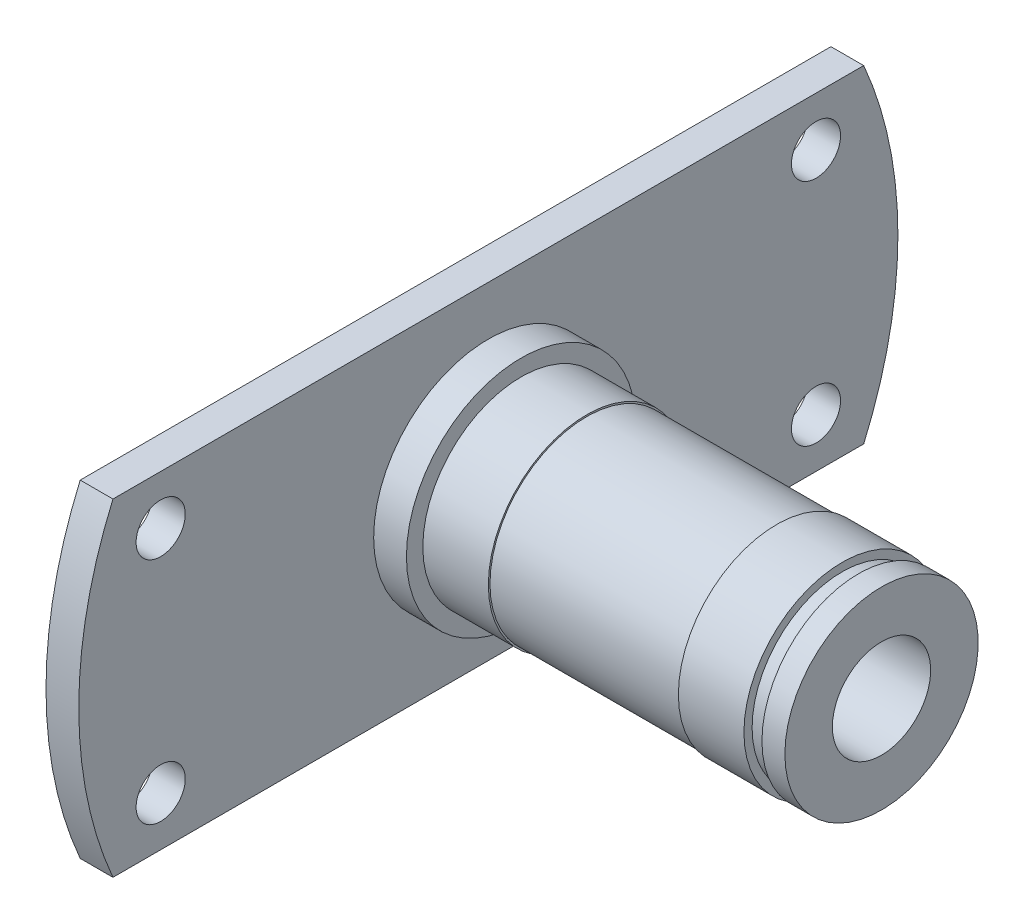
SolidWorks part; units mm, degrees
material "6063-T6"
ref_plane "前视基准面" through (0, 0, 0) normal (0, 0, 1) x (1, 0, 0)
ref_plane "上视基准面" through (0, 0, 0) normal (0, 1, 0) x (1, 0, 0)
ref_plane "右视基准面" through (0, 0, 0) normal (1, 0, 0) x (0, 0, -1)
sketch "草图1" plane through (0, 0, 0) normal (0, 0, 1) x (1, 0, 0)
  line L0 (-38.4052, 0) -> (36.2929, 0) construction
  line L1 (0, 6) -> (0, 7)
  line L2 (0, 6) -> (4, 6)
  line L3 (4, 6) -> (4, 5.9)
  line L4 (4, 5.9) -> (15.6, 5.9)
  line L5 (15.6, 5.9) -> (15.6, 6)
  line L6 (15.6, 6) -> (19.6, 6)
  line L7 (19.6, 6) -> (19.6, 5.5)
  line L8 (19.6, 5.5) -> (20.6, 5.5)
  line L9 (20.6, 5.5) -> (20.6, 5.9)
  line L10 (20.6, 5.9) -> (22, 5.9)
  line L11 (22, 5.9) -> (22, 3)
  line L12 (-2, 0) -> (28, 0)
  line L13 (0, 7) -> (-2, 7)
  line L14 (-2, 7) -> (-2, 0)
  line L15 (22, 3) -> (28, 3) construction
  line L16 (22, 3) -> (22, 0)
  line L19 (28, 0) -> (28, 3) construction
  dimension "D1" = 12
  dimension "D2" = 11.8
  dimension "D3" = 14
  dimension "D4" = 4
  dimension "D5" = 4
  dimension "D6" = 1
  dimension "D7" = 1.4
  dimension "D8" = 11
  dimension "D9" = 2
  dimension "D10" = 19.6
  dimension "D11" = 6
  dimension "D12" = 6
revolve "旋转2" add sketch "草图1" angle 360 about L0
sketch "草图2" plane through (-2, 0, 0) normal (-1, 0, 0) x (0, 0, 1)
  line L0 (0, 0) -> (0, 14.6891) construction
  line L1 (0, 0) -> (25, 0) construction
  circle A0 centre (0, 0) radius 25
  circle A1 centre (-20, 7) radius 1.5
  circle A2 centre (20, 7) radius 1.5
  circle A3 centre (20, -7) radius 1.5
  circle A4 centre (-20, -7) radius 1.5
  dimension "D1" = 50
  dimension "D2" = 3
  dimension "D3" = 40
  dimension "D4" = 14
extrude "凸台-拉伸1" add sketch "草图2" along normal blind 2
sketch "草图5" plane through (-2, 0, 0) normal (1, 0, 0) x (0, 0, -1)
  line L0 (0, 0) -> (0, 27.6852) construction
  line L1 (-22.9129, 25) -> (22.9129, 25)
  line L2 (-22.9129, 25) -> (-22.9129, 10)
  line L3 (-22.9129, 10) -> (22.9129, 10)
  line L4 (22.9129, 25) -> (22.9129, 10)
  circle A0 centre (20, 7) radius 1.5 construction
  circle A1 centre (0, 0) radius 25 construction
  circle A2 centre (0, 0) radius 25 construction
  point P6 (0, 10)
  dimension "D1" = 3
extrude "切除-拉伸2" cut sketch "草图5" against normal up to next
mirror "镜向1" about plane through (0, 0, 0) normal (0, 1, 0) of "切除-拉伸2"
hole_wizard "Ø6.0 (6) 直径孔1" positions "草图7" profile "草图6" hole size "Ø6.0" standard "GB" end condition through all
sketch "草图7" plane through (-4, 0, 0) normal (-1, 0, 0) x (0, 0, 1)
  point P0 (0, 0)
sketch "草图6" plane through (-4, 0, 0) normal (0, 1, 0) x (0, 0, 1)
  line L0 (0, 0) -> (0, 26)
  line L1 (0, 26) -> (3, 26)
  line L2 (3, 26) -> (3, 0)
  line L5 (3, 0) -> (0, 0)
  line L11 (0, -6.35) -> (0, 107.95) construction
  dimension "通孔孔直径" = 6
  dimension "通孔孔深度" = 26
move or copy body "实体-移动/复制1" [suppressed] bodies to move or copy 114
